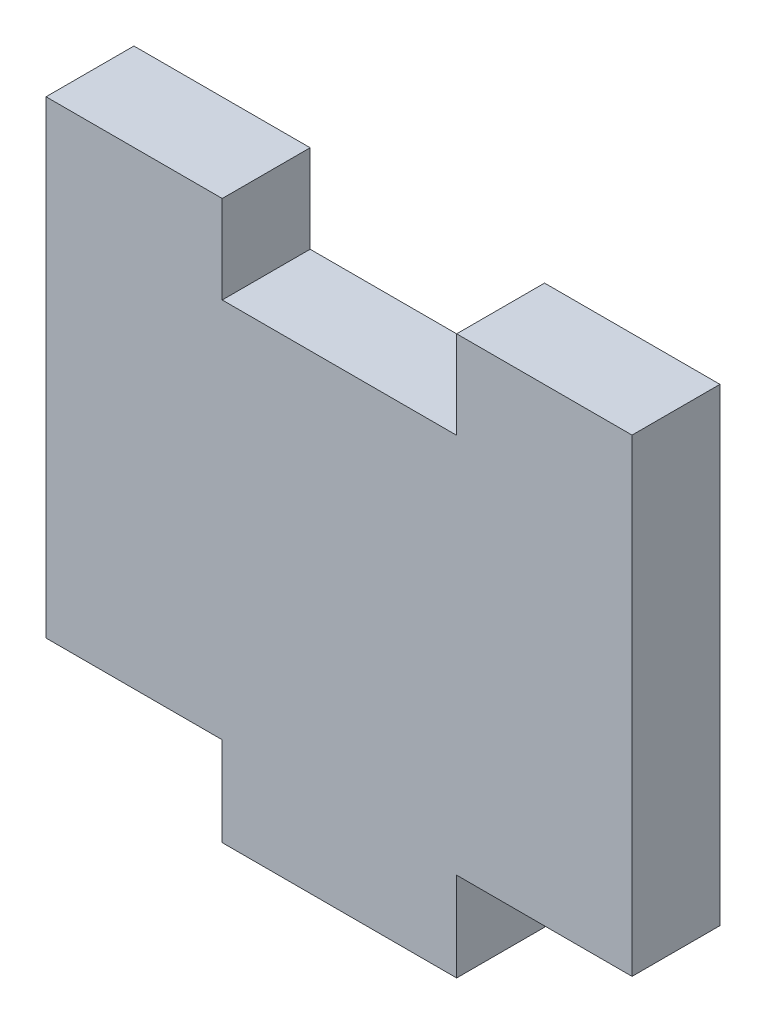
SolidWorks part; units mm, degrees
ref_plane "Front Plane" through (0, 0, 0) normal (0, 0, 1) x (1, 0, 0)
ref_plane "Top Plane" through (0, 0, 0) normal (0, 1, 0) x (1, 0, 0)
ref_plane "Right Plane" through (0, 0, 0) normal (1, 0, 0) x (0, 0, -1)
sketch "Sketch1" plane through (0, 0, 0) normal (0, 0, 1) x (1, 0, 0)
  line L0 (31.7935, -9.652) -> (31.7935, 0) construction
  line L1 (0, 0) -> (19.0935, 0)
  line L2 (0, 0) -> (0, 50.8)
  line L3 (0, 50.8) -> (19.0935, 50.8)
  line L4 (63.5, 0) -> (63.5, 12.7)
  line L6 (19.0935, 0) -> (19.0935, -9.652)
  line L7 (19.0935, -9.652) -> (44.4935, -9.652)
  line L8 (44.4935, 0) -> (44.4935, -9.652)
  line L9 (44.4935, 0) -> (63.5, 0)
  line L10 (63.5, 38.1) -> (63.5, 12.7)
  line L15 (63.5, 38.1) -> (63.5, 50.8)
  line L16 (44.4935, 50.8) -> (63.5, 50.8)
  line L18 (19.0935, 50.8) -> (19.0935, 41.275)
  line L19 (19.0935, 41.275) -> (44.4935, 41.275)
  line L20 (44.4935, 50.8) -> (44.4935, 41.275)
  dimension "D1" = 63.5
  dimension "D2" = 50.8
  dimension "D3" = 9.652
  dimension "D4" = 25.4
  dimension "D7" = 25.4
  dimension "D8" = 9.525
extrude "Boss-Extrude1" add sketch "Sketch1" along normal blind 9.525
